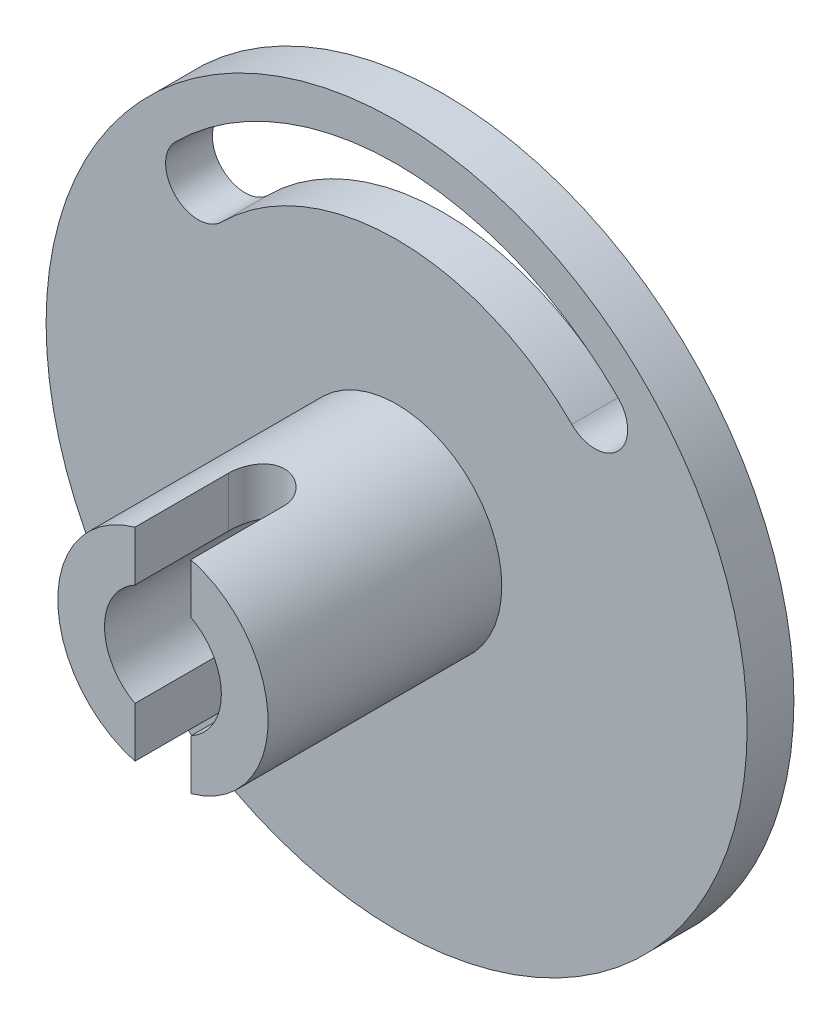
SolidWorks part; units mm, degrees
ref_plane "Front Plane" through (0, 0, 0) normal (0, 0, 1) x (1, 0, 0)
ref_plane "Top Plane" through (0, 0, 0) normal (0, 1, 0) x (1, 0, 0)
ref_plane "Right Plane" through (0, 0, 0) normal (1, 0, 0) x (0, 0, -1)
sketch "Sketch1" plane through (0, 0, 0) normal (0, 0, 1) x (1, 0, 0)
  circle A0 centre (0, 0) radius 75
  dimension "D1" = 150
extrude "Boss-Extrude1" add sketch "Sketch1" along normal blind 10 contours A0
sketch "Sketch2" plane through (0, 0, 10) normal (0, 0, 1) x (1, 0, 0)
  circle A0 centre (0, 0) radius 22.5
  dimension "D1" = 45
extrude "Boss-Extrude2" add sketch "Sketch2" along normal blind 50
sketch "Sketch3" plane through (0, 0, 0) normal (0, 1, 0) x (1, 0, 0)
  line L0 (0, -40) -> (0, -60) construction
  line L1 (6, -40) -> (6, -60)
  line L2 (-6, -40) -> (-6, -60)
  line L3 (-22.5, -60) -> (22.5, -60) construction
  arc A0 (6, -40) -> (-6, -40) centre (0, -40) ccw
  arc A1 (-6, -60) -> (6, -60) centre (0, -60) ccw
  point P3 (0, -50)
  dimension "D1" = 6
  dimension "D2" = 20
extrude "Cut-Extrude1" cut sketch "Sketch3" against normal mid plane 60
sketch "Sketch4" plane through (0, 0, 10) normal (0, 0, 1) x (1, 0, 0)
  line L0 (0, 0) -> (47.3762, 47.3762) construction
  line L1 (0, 0) -> (0, 67) construction
  line L2 (0, 0) -> (-47.3762, 47.3762) construction
  arc A0 (37.4767, 37.4767) -> (-37.4767, 37.4767) centre (0, 0) ccw
  arc A1 (47.3762, 47.3762) -> (-47.3762, 47.3762) centre (0, 0) ccw
  arc A2 (42.4264, 42.4264) -> (-42.4264, 42.4264) centre (0, 0) ccw construction
  arc A3 (-37.4767, 37.4767) -> (-47.3762, 47.3762) centre (-42.4264, 42.4264) cw
  arc A4 (37.4767, 37.4767) -> (47.3762, 47.3762) centre (42.4264, 42.4264) ccw
  dimension "D2" = 120
  dimension "D3" = 7
  dimension "D1" = 90
extrude "Cut-Extrude2" cut sketch "Sketch4" against normal through all
sketch "Sketch5" plane through (0, 0, 60) normal (0, 0, 1) x (1, 0, 0)
  circle A0 centre (0, 0) radius 12.5
  dimension "D1" = 25
extrude "Cut-Extrude3" cut sketch "Sketch5" against normal through all
